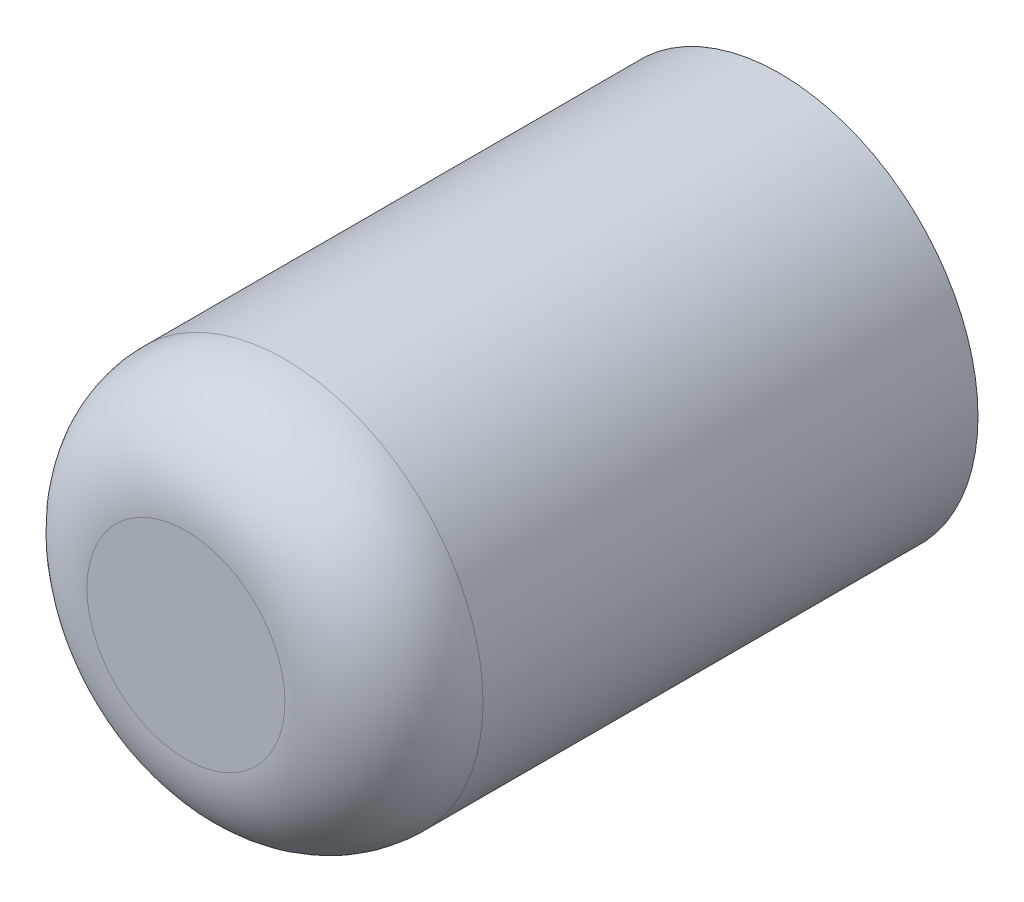
SolidWorks part; units mm, degrees
ref_plane "前视基准面" through (0, 0, 0) normal (0, 0, 1) x (1, 0, 0)
ref_plane "上视基准面" through (0, 0, 0) normal (0, 1, 0) x (1, 0, 0)
ref_plane "右视基准面" through (0, 0, 0) normal (1, 0, 0) x (0, 0, -1)
sketch "草图1" plane through (0, 0, 0) normal (0, 0, 1) x (1, 0, 0)
  circle A0 centre (0, 0) radius 2
extrude "凸台-拉伸1" add sketch "草图1" along normal blind 6
fillet "圆角1" radius 1 1 edges at (2, 0, 6)
sketch "草图2" plane through (0, 0, 0) normal (0, 0, -1) x (-1, 0, 0)
  line L1 (1.1547, 0) -> (0.5774, 1)
  line L2 (0.5774, 1) -> (-0.5774, 1)
  line L3 (-0.5774, 1) -> (-1.1547, 0)
  line L4 (-1.1547, 0) -> (-0.5774, -1)
  line L5 (-0.5774, -1) -> (0.5774, -1)
  line L6 (0.5774, -1) -> (1.1547, 0)
  circle A0 centre (0, 0) radius 1 construction
extrude "切除-拉伸1" cut sketch "草图2" against normal blind 1.5
